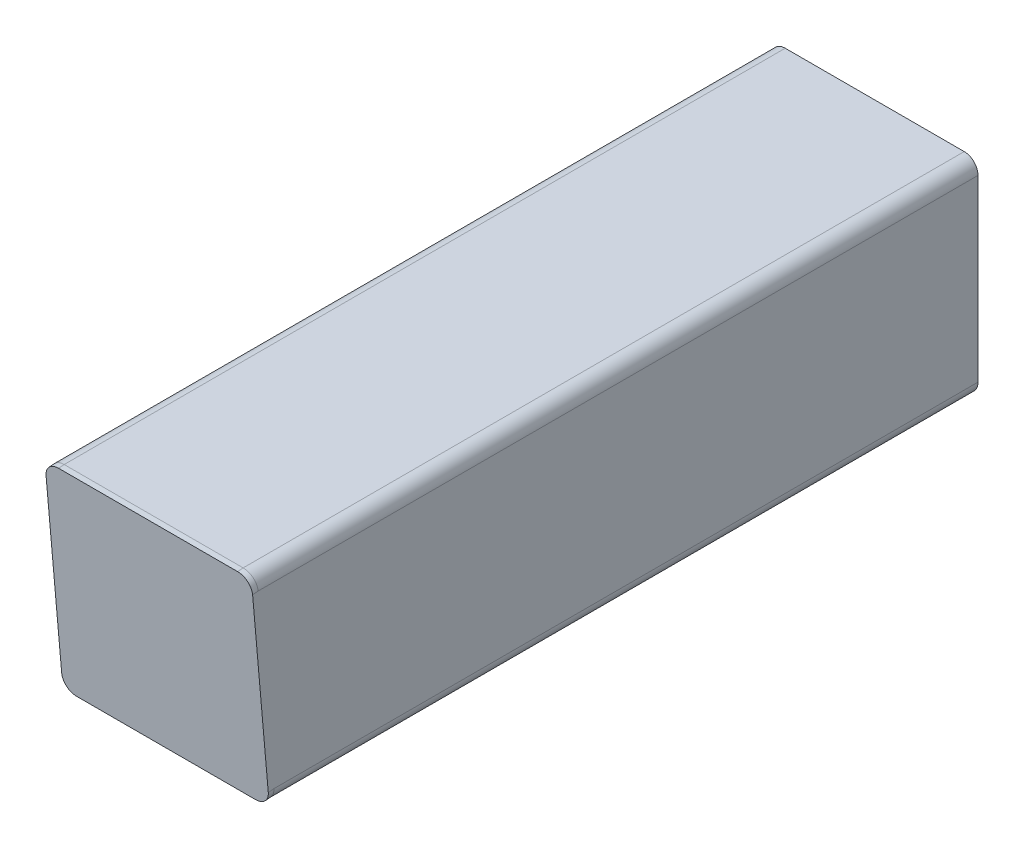
SolidWorks part; units mm, degrees
material "ASTM A500 Grade B Steel"
ref_plane "Front Plane" through (0, 0, 0) normal (0, 0, 1) x (1, 0, 0)
ref_plane "Top Plane" through (0, 0, 0) normal (0, 1, 0) x (1, 0, 0)
ref_plane "Right Plane" through (0, 0, 0) normal (1, 0, 0) x (0, 0, -1)
sketch "Sketch1" plane through (0, 0, 0) normal (0, 0, 1) x (1, 0, 0)
  line L0 (5.3086, -2.7686) -> (32.7914, -2.7686)
  line L1 (2.54, 0) -> (35.56, 0)
  line L2 (0, -2.54) -> (0, -35.56)
  line L3 (2.54, -38.1) -> (35.56, -38.1)
  line L4 (38.1, -2.54) -> (38.1, -35.56)
  line L5 (35.3314, -5.3086) -> (35.3314, -32.7914)
  line L6 (5.3086, -35.3314) -> (32.7914, -35.3314)
  line L7 (2.7686, -5.3086) -> (2.7686, -32.7914)
  line L8 (0, 0) -> (0, -38.1) construction
  line L9 (0, -38.1) -> (38.1, -38.1) construction
  line L10 (38.1, 0) -> (38.1, -38.1) construction
  line L11 (2.7686, -2.7686) -> (2.7686, -35.3314) construction
  line L12 (2.7686, -35.3314) -> (35.3314, -35.3314) construction
  line L13 (35.3314, -2.7686) -> (35.3314, -35.3314) construction
  line L14 (2.7686, -2.7686) -> (35.3314, -2.7686) construction
  line L15 (0, 0) -> (38.1, 0) construction
  arc A0 (0, -35.56) -> (2.54, -38.1) centre (2.54, -35.56) ccw
  arc A1 (38.1, -35.56) -> (35.56, -38.1) centre (35.56, -35.56) cw
  arc A2 (2.7686, -32.7914) -> (5.3086, -35.3314) centre (5.3086, -32.7914) ccw
  arc A3 (32.7914, -35.3314) -> (35.3314, -32.7914) centre (32.7914, -32.7914) ccw
  arc A4 (35.3314, -5.3086) -> (32.7914, -2.7686) centre (32.7914, -5.3086) ccw
  arc A5 (38.1, -2.54) -> (35.56, 0) centre (35.56, -2.54) ccw
  arc A6 (0, -2.54) -> (2.54, 0) centre (2.54, -2.54) cw
  arc A7 (5.3086, -2.7686) -> (2.7686, -5.3086) centre (5.3086, -5.3086) ccw
  point P12 (0, -38.1)
  dimension "D4" = 2.54
  dimension "D3" = 2.7686
extrude "Boss-Extrude1" add sketch "Sketch1" along normal blind 133
sketch "Sketch2" plane through (38.1, 0, 0) normal (1, 0, 0) x (0, 0, -1)
  line L0 (-133, 0) -> (-129.6667, -38.1)
  line L1 (-133, -38.1) -> (0, -38.1) construction
  line L2 (-129.6667, -38.1) -> (-133, -38.1)
  line L3 (-133, -38.1) -> (-133, 0)
  dimension "D1" = 5
extrude "Cut-Extrude1" cut sketch "Sketch2" against normal through all
sketch "Sketch3" plane through (0, -11.5476, 131.9897) normal (0, -0.0872, 0.9962) x (1, 0, 0)
  line L4 (2.54, -26.6538) -> (35.56, -26.6538)
  line L5 (38.1, -24.1041) -> (38.1, 9.042)
  line L6 (35.56, 11.5917) -> (2.54, 11.5917)
  line L7 (0, 9.042) -> (0, -24.1041)
  line L8 (2.54, -26.6538) -> (35.56, -26.6538)
  line L9 (38.1, -24.1041) -> (38.1, 9.042)
  line L10 (35.56, 11.5917) -> (2.54, 11.5917)
  line L11 (0, 9.042) -> (0, -24.1041)
  ellipse E4 centre (35.56, -24.1041) end of major axis (35.56, -26.6538) minor radius 2.54 (35.56, -26.6538) -> (38.1, -24.1041) ccw
  ellipse E5 centre (35.56, 9.042) end of major axis (35.56, 6.4923) minor radius 2.54 (38.1, 9.042) -> (35.56, 11.5917) ccw
  ellipse E6 centre (2.54, 9.042) end of major axis (2.54, 11.5917) minor radius 2.54 (2.54, 11.5917) -> (0, 9.042) ccw
  ellipse E7 centre (2.54, -24.1041) end of major axis (2.54, -26.6538) minor radius 2.54 (0, -24.1041) -> (2.54, -26.6538) ccw
  ellipse E8 centre (35.56, -24.1041) end of major axis (35.56, -26.6538) minor radius 2.54 (35.56, -26.6538) -> (38.1, -24.1041) ccw
  ellipse E9 centre (35.56, 9.042) end of major axis (35.56, 6.4923) minor radius 2.54 (38.1, 9.042) -> (35.56, 11.5917) ccw
  ellipse E10 centre (2.54, 9.042) end of major axis (2.54, 11.5917) minor radius 2.54 (2.54, 11.5917) -> (0, 9.042) ccw
  ellipse E11 centre (2.54, -24.1041) end of major axis (2.54, -26.6538) minor radius 2.54 (0, -24.1041) -> (2.54, -26.6538) ccw
  dimension "D1" = 0
extrude "Boss-Extrude2" add sketch "Sketch3" along normal up to surface (1.0222 mm away)
